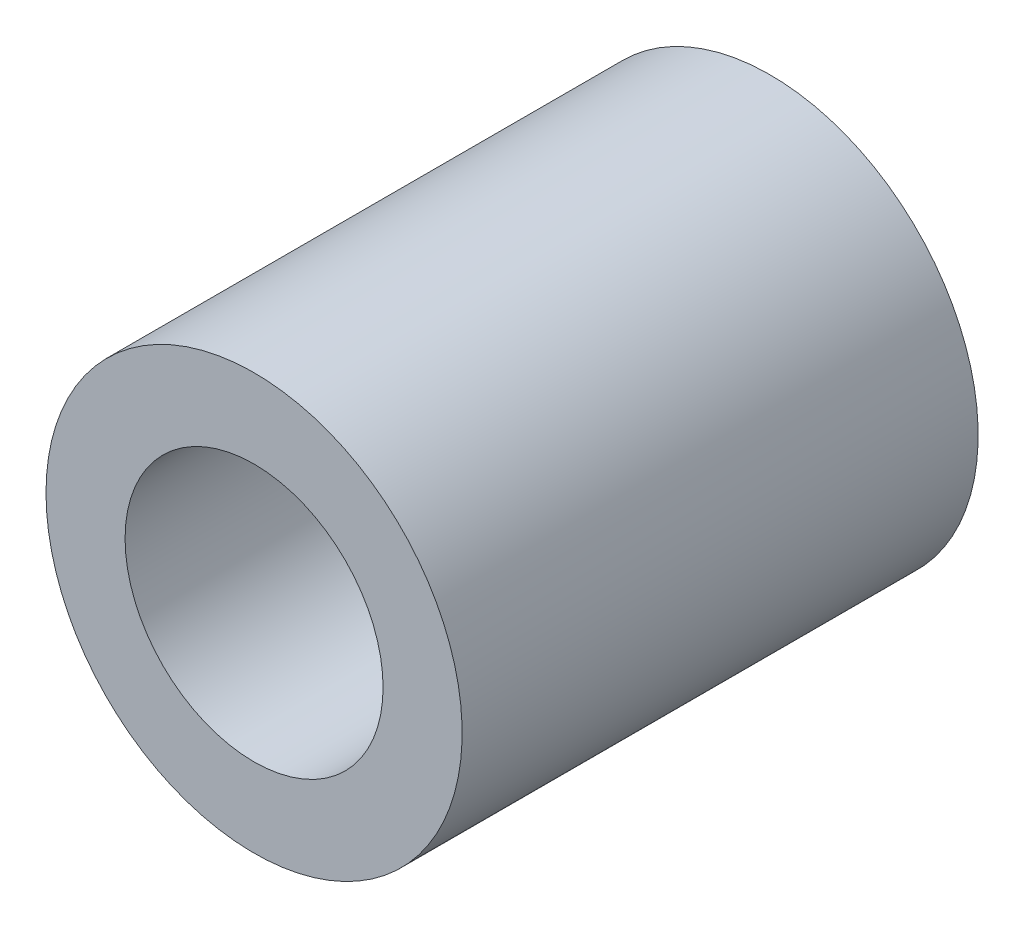
SolidWorks part; units mm, degrees
ref_plane "Front Plane" through (0, 0, 0) normal (0, 0, 1) x (1, 0, 0)
ref_plane "Top Plane" through (0, 0, 0) normal (0, 1, 0) x (1, 0, 0)
ref_plane "Right Plane" through (0, 0, 0) normal (1, 0, 0) x (0, 0, -1)
sketch "Sketch1" plane through (0, 0, 0) normal (0, 0, 1) x (1, 0, 0)
  circle A0 centre (0, 0) radius 2.5
  circle A1 centre (0, 0) radius 1.55
  dimension "D1" = 5
  dimension "D2" = 3.1
extrude "Boss-Extrude1" add sketch "Sketch1" along normal blind 6.2
